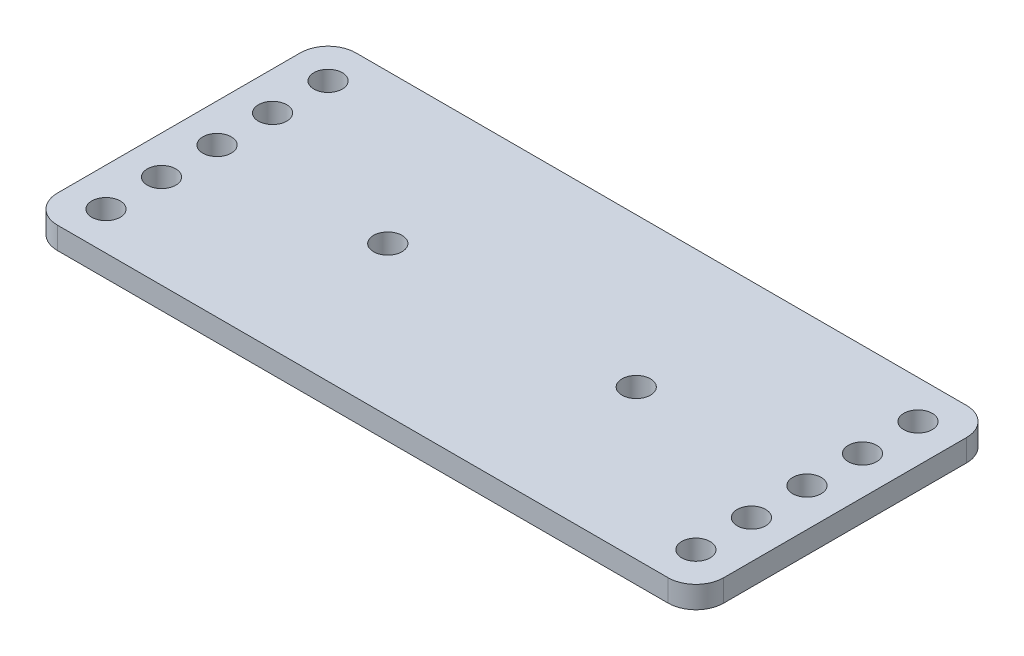
SolidWorks part; units mm, degrees
ref_plane "Front Plane" through (0, 0, 0) normal (0, 0, 1) x (1, 0, 0)
ref_plane "Top Plane" through (0, 0, 0) normal (0, 1, 0) x (1, 0, 0)
ref_plane "Right Plane" through (0, 0, 0) normal (1, 0, 0) x (0, 0, -1)
sketch "Sketch1" plane through (0, 0, 0) normal (0, 1, 0) x (1, 0, 0)
  line L0 (0, 0) -> (50000, 0) construction
  line L1 (48, -21.5) -> (-48, -21.5)
  line L2 (48, -21.5) -> (48, 21.5)
  line L3 (48, 21.5) -> (-48, 21.5)
  line L4 (-48, -21.5) -> (-48, 21.5)
  line L5 (48, -21.5) -> (-48, 21.5) construction
  line L6 (48, 21.5) -> (-48, -21.5) construction
  line L7 (0.4, 18.05) -> (3.4, 18.05) construction
  line L8 (35.4, -16) -> (0.4, -16) construction
  line L9 (35.4, -16) -> (35.4, 16) construction
  line L10 (35.4, 16) -> (0.4, 16) construction
  line L11 (0.4, -16) -> (0.4, 16) construction
  line L12 (35.4, -16) -> (0.4, 16) construction
  line L13 (35.4, 16) -> (0.4, -16) construction
  line L14 (0.4, 13.95) -> (3.4, 13.95) construction
  line L15 (17.9, 56.2389) -> (17.9, -49943.7611) construction
  line L16 (0.4, -13.95) -> (3.4, -13.95) construction
  line L17 (0.4, -18.05) -> (3.4, -18.05) construction
  line L18 (-42.5, -19.9024) -> (-42.5, -1.0474) construction
  line L19 (35.4, -18.05) -> (32.4, -18.05) construction
  line L20 (35.4, -13.95) -> (32.4, -13.95) construction
  line L21 (35.4, 13.95) -> (32.4, 13.95) construction
  line L22 (35.4, 18.05) -> (32.4, 18.05) construction
  line L23 (-42.5, 16) -> (-42.5, 8) construction
  line L24 (0, -21.5) -> (0, 49978.5) construction
  circle A0 centre (-17.9, 0) radius 18 construction
  circle A1 centre (17.9, 0) radius 18 construction
  arc A2 (0.4, 18.05) -> (0.4, 13.95) centre (0.4, 16) ccw construction
  arc A4 (0.4, -18.05) -> (0.4, -13.95) centre (0.4, -16) cw construction
  arc A5 (3.4, 13.95) -> (3.4, 18.05) centre (3.4, 16) ccw construction
  arc A6 (3.4, -13.95) -> (3.4, -18.05) centre (3.4, -16) cw construction
  arc A7 (35.4, -18.05) -> (35.4, -13.95) centre (35.4, -16) ccw construction
  arc A8 (32.4, -13.95) -> (32.4, -18.05) centre (32.4, -16) ccw construction
  arc A9 (35.4, 18.05) -> (35.4, 13.95) centre (35.4, 16) cw construction
  arc A10 (32.4, 13.95) -> (32.4, 18.05) centre (32.4, 16) cw construction
  circle A11 centre (17.9, 0) radius 8.05 construction
  circle A12 centre (-17.9, 0) radius 2.05
  circle A13 centre (-17.9, 0) radius 19 construction
  circle A14 centre (-42.5, 16) radius 2.05
  circle A15 centre (-42.5, 8) radius 2.05
  circle A16 centre (-42.5, 0) radius 2.05
  circle A17 centre (-42.5, -8) radius 2.05
  circle A18 centre (-42.5, -16) radius 2.05
  circle A19 centre (42.5, 16) radius 2.05
  circle A20 centre (42.5, 8) radius 2.05
  circle A21 centre (42.5, 0) radius 2.05
  circle A22 centre (42.5, -8) radius 2.05
  circle A23 centre (42.5, -16) radius 2.05
  circle A24 centre (17.9, 0) radius 2.05
  point P0 (0, 0)
  point P57 (0, -21.5)
  dimension "D4" = 36
  dimension "D8" = 4.1
  dimension "D11" = 16.1
  dimension "D12" = 38
  dimension "D14" = 4.1
  dimension "D18" = 4.1
  dimension "D1" = 96
  dimension "D2" = 43
  dimension "D3" = 35.8
  dimension "D5" = 17.9
  dimension "D6" = 35
  dimension "D7" = 32
  dimension "D9" = 3
  dimension "D13" = 5.5
  dimension "D15" = 5.5
  dimension "D17" = 8
  dimension "D16" = 5
extrude "Boss-Extrude1" add sketch "Sketch1" along normal blind 3.175
fillet "Fillet1" radius 4 4 edges at (48, 1.5875, 21.5) (48, 1.5875, -21.5) (-48, 1.5875, -21.5) (-48, 1.5875, 21.5)
equation "\"w\"= 43mm"
equation "\"h\"= 96mm"
equation "\"pitchDiameter\"= 36mm'45 Tooth Hub-Mount Gear"
equation "\"servoBlockLargeCenterDistance\"= 35mm"
equation "\"cent2cent\"= 35.8mm"
equation "\"servoBlockLargeCenterDistanceheight\"= 32mm"
equation "\"sh\"= 4.1mm"
equation "\"D1@Sketch1\"=\"h\""
equation "\"D2@Sketch1\"=\"w\""
equation "\"D4@Sketch1\"=\"pitchDiameter\""
equation "\"D5@Sketch1\"=\"cent2cent\"/2"
equation "\"D6@Sketch1\"=\"servoBlockLargeCenterDistance\""
equation "\"D7@Sketch1\"=\"servoBlockLargeCenterDistanceheight\""
equation "\"D8@Sketch1\"=\"sh\""
equation "\"D9@Sketch1\"=3"
equation "\"bearingOD\"= 14.1mm"
equation "\"thick\"= 3.175mm"
equation "\"D11@Sketch1\"=\"bearingOD\"+2"
equation "\"D1@Boss-Extrude1\"=\"thick\""
equation "\"D14@Sketch1\"=\"sh\""
equation "\"D18@Sketch1\"=\"sh\""
